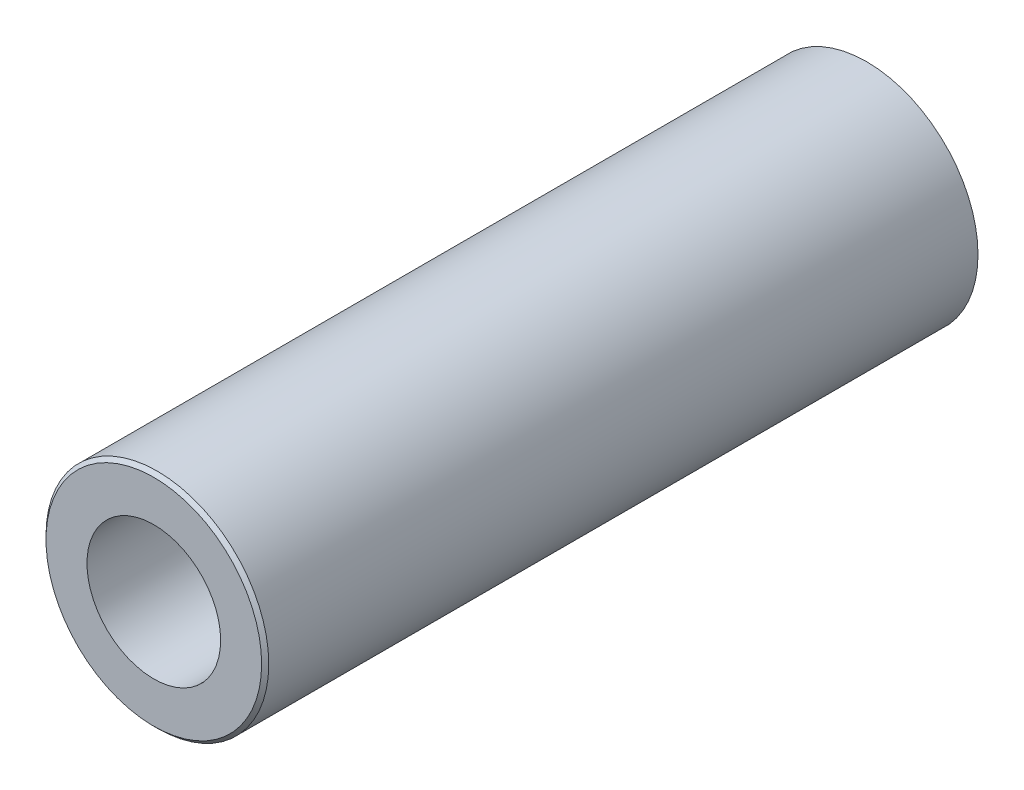
SolidWorks part; units mm, degrees
material "AISI 4130 Steel, annealed at 865C"
ref_plane "Front" through (0, 0, 0) normal (0, 0, 1) x (1, 0, 0)
ref_plane "Top" through (0, 0, 0) normal (0, 1, 0) x (1, 0, 0)
ref_plane "Right" through (0, 0, 0) normal (1, 0, 0) x (0, 0, -1)
sketch "Sketch1" plane through (0, 0, 0) normal (0, 0, 1) x (1, 0, 0)
  circle A0 centre (0, 0) radius 7.9375
  dimension "D1" = 15.875
extrude "Boss-Extrude1" add sketch "Sketch1" along normal blind 50.8
chamfer "Chamfer1" distance 0.254 angle 45 1 edges at (7.9375, 0, 50.8)
sketch "Sketch2" plane through (0, 0, 0) normal (0, 0, -1) x (-1, 0, 0)
  circle A0 centre (0, 0) radius 6.4643
  circle A1 centre (0, 0) radius 7.9375 construction
  dimension "D1" = 1.4732
sketch "Sketch4" [suppressed] plane through (0, 0, 19.05) normal (0, 0, 1) x (1, 0, 0)
  line L1 (6.4158, 0) -> (3.2079, 5.5563)
  line L2 (3.2079, 5.5563) -> (-3.2079, 5.5563)
  line L3 (-3.2079, 5.5563) -> (-6.4158, 0)
  line L4 (-6.4158, 0) -> (-3.2079, -5.5563)
  line L5 (-3.2079, -5.5563) -> (3.2079, -5.5563)
  line L6 (3.2079, -5.5563) -> (6.4158, 0)
  circle A0 centre (0, 0) radius 5.5562 construction
  circle A1 centre (0, 0) radius 6.35 construction
  circle A2 centre (0, 0) radius 6.35
  dimension "D1" = 11.1125
extrude "Cut-Extrude3" [suppressed] cut sketch "Sketch4" against normal blind 5.5562
hole_wizard "Tap Drill for 3/8-24 Tap1" [suppressed] positions "Sketch5" profile "Sketch6" hole size "3/8-24" standard "ANSI Inch"
sketch "Sketch5" plane through (0, 0, 15.875) normal (0, 0, 1) x (1, 0, 0)
  point P0 (0, 0)
sketch "Sketch6" plane through (0, 0, 15.875) normal (1, 0, 0) x (0, -1, 0)
  line L0 (0, 0) -> (0, 15.875)
  line L1 (0, 15.875) -> (4.2164, 15.875)
  line L2 (4.2164, 15.875) -> (4.2164, 0)
  line L5 (4.2164, 0) -> (0, 0)
  line L11 (0, -6.35) -> (0, 107.95) construction
  dimension "Thru Hole Dia." = 8.4328
  dimension "Thru Hole Depth" = 15.875
hole_wizard "5/16 (0.3125) Dowel Hole1" positions "Sketch7" profile "Sketch8" hole size "5/16" standard "ANSI Inch" end condition through all
sketch "Sketch7" plane through (0, 0, 50.8) normal (0, 0, 1) x (1, 0, 0)
  point P0 (0, 0)
sketch "Sketch8" plane through (0, 0, 50.8) normal (1, 0, 0) x (0, -1, 0)
  line L0 (0, 0) -> (0, 50.8)
  line L1 (0, 50.8) -> (4.7625, 50.8)
  line L2 (4.7625, 50.8) -> (4.7625, 0)
  line L5 (4.7625, 0) -> (0, 0)
  line L11 (0, -6.35) -> (0, 107.95) construction
  dimension "Thru Hole Dia." = 9.525
  dimension "Thru Hole Depth" = 50.8
hole_wizard "Tap Drill for 1/4-28 Tap1" [suppressed] positions "Sketch9" profile "Sketch10" hole size "1/4-28" standard "ANSI Inch"
sketch "Sketch9" plane through (0, 0, 19.05) normal (0, 0, 1) x (1, 0, 0)
  point P0 (0, 0)
sketch "Sketch10" plane through (0, 0, 19.05) normal (1, 0, 0) x (0, -1, 0)
  line L0 (0, 0) -> (0, 19.05)
  line L1 (0, 19.05) -> (2.7051, 19.05)
  line L2 (2.7051, 19.05) -> (2.7051, 0)
  line L5 (2.7051, 0) -> (0, 0)
  line L11 (0, -6.35) -> (0, 107.95) construction
  dimension "Thru Hole Dia." = 5.4102
  dimension "Thru Hole Depth" = 19.05
equation "\"Tube Radius\"= 5 / 16in"
equation "\"Wall Thickness\"= 0.058"
equation "\"D1@Sketch1\"= 2 * \"Tube Radius\""
equation "\"D1@Sketch2\" = \"Wall Thickness\""
